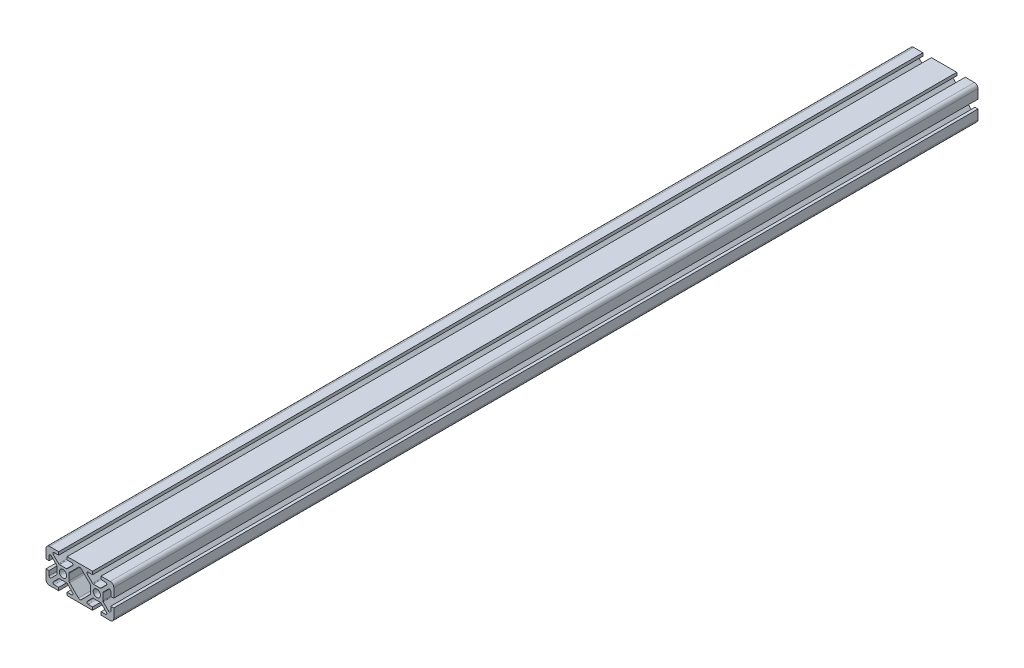
SolidWorks part; units mm, degrees
ref_plane "Front Plane" through (0, 0, 0) normal (0, 0, 1) x (1, 0, 0)
ref_plane "Top Plane" through (0, 0, 0) normal (0, 1, 0) x (1, 0, 0)
ref_plane "Right Plane" through (0, 0, 0) normal (1, 0, 0) x (0, 0, -1)
sketch "Sketch1" plane through (0, 0, 0) normal (0, 0, 1) x (1, 0, 0)
  line L0 (10, 10) -> (10, -10) construction
  line L1 (-20, 0) -> (20, 0) construction
  line L2 (12.5, -10) -> (20, -10)
  line L3 (20, -10) -> (20, -2.5)
  line L4 (12.5, -10) -> (12.5, -8.2134)
  line L5 (12.5, -8.2134) -> (16.95, -8.2134)
  line L6 (16.95, -8.2134) -> (12.3366, -3.6)
  line L7 (10, 0) -> (20, -10) construction
  line L8 (20, -2.5) -> (18.2134, -2.5)
  line L9 (18.2134, -2.5) -> (18.2134, -6.95)
  line L10 (18.2134, -6.95) -> (13.6, -2.3366)
  line L11 (15.9067, -4.6433) -> (14.6433, -5.9067) construction
  line L12 (0, 10) -> (0, -10) construction
  line L13 (0, -10) -> (-20, -10) construction
  line L14 (-10, 10) -> (10, 10) construction
  line L15 (20, 2.5) -> (20, -2.5) construction
  circle A0 centre (10, 0) radius 2.15
  arc A1 (15.5015, -8.2134) -> (15.9257, -7.1891) centre (15.5015, -7.6134) ccw construction
  point P8 (10, -3.6)
  point P16 (15.275, -5.275)
  point P30 (20, 0)
  dimension "Center Hole Diameter" = 4.3
  dimension "D3" = 0.6
  dimension "Rail Width" = 20
  dimension "T-Slot Width" = 5
  dimension "Slot Depth" = 6.4
  dimension "Rail Height" = 40
  dimension "Inner Slot Width" = 13.9
  dimension "Hole Spacing" = 20
sketch "Sketch2" plane through (0, 0, 0) normal (1, 0, 0) x (0, 0, -1)
  line L0 (-1524, -10) -> (1524, -10) construction
  line L1 (-1484, 0) -> (1484, 0) construction
  point P6 (-1484, 0)
  point P8 (1484, 0)
  dimension "Length" = 3048
  dimension "D1" = 40
sketch "Sketch3" plane through (0, 0, 0) normal (0, 0, 1) x (1, 0, 0)
  line L0 (12.5, -10) -> (17.9, -10)
  line L1 (12.5, -10) -> (20, -10) construction
  line L2 (12.5, -10) -> (12.5, -8.2134) construction
  line L3 (12.5, -8.2134) -> (16.95, -8.2134) construction
  line L4 (12.5, -8.2134) -> (12.5, -10)
  line L5 (12.5, -8.2134) -> (16.95, -8.2134)
  line L6 (10, -3.6) -> (12.3366, -3.6)
  line L7 (16.95, -8.2134) -> (12.3366, -3.6) construction
  line L8 (12.3366, -3.6) -> (16.95, -8.2134)
  line L9 (20, -10) -> (20, -2.5) construction
  line L10 (18.2134, -6.95) -> (13.6, -2.3366) construction
  line L11 (18.2134, -2.5) -> (18.2134, -6.95) construction
  line L12 (18.2134, -6.95) -> (18.2134, -2.5)
  line L13 (20, -2.5) -> (18.2134, -2.5) construction
  line L14 (18.2134, -2.5) -> (20, -2.5)
  line L15 (20, -2.5) -> (20, -7.9)
  line L16 (18.2134, -6.95) -> (13.6, -2.3366)
  line L17 (13.6, 0) -> (13.6, -2.3366)
  line L18 (-20, 0) -> (20, 0) construction
  line L19 (10, -3.6) -> (10, -2.15)
  line L20 (10, 10) -> (10, -10) construction
  line L21 (13.6, 0) -> (12.15, 0)
  arc A5 (17.9, -10) -> (20, -7.9) centre (17.9, -7.9) ccw
  circle A10 centre (10, 0) radius 2.15 construction
  arc A11 (10, -2.15) -> (12.15, 0) centre (10, 0) ccw
  dimension "D1" = 2.1
extrude "Boss-Extrude1" add sketch "Sketch3" along normal mid plane 3048
sketch "Sketch4" plane through (0, 0, 0) normal (0, 0, 1) x (1, 0, 0)
  line L0 (10, -3.6) -> (7.6634, -3.6)
  line L4 (7.6634, -3.6) -> (3.05, -8.2134)
  line L5 (3.05, -8.2134) -> (7.5, -8.2134)
  line L6 (7.5, -8.2134) -> (7.5, -10)
  line L18 (7.5, -10) -> (0, -10)
  line L19 (12.5, -10) -> (12.5, -8.2134) construction
  line L20 (12.5, -8.2134) -> (16.95, -8.2134) construction
  line L21 (10, -3.6) -> (12.3366, -3.6) construction
  line L22 (16.95, -8.2134) -> (12.3366, -3.6) construction
  line L23 (0, -8.7366) -> (6.4, -2.3366)
  line L24 (0, 10) -> (0, -10) construction
  line L25 (6.4, -2.3366) -> (6.4, 0)
  line L26 (-20, 0) -> (20, 0) construction
  line L27 (6.4, 0) -> (7.85, 0)
  line L28 (13.6, 0) -> (12.15, 0) construction
  line L29 (0, -8.7366) -> (0, -10)
  line L30 (10, -2.15) -> (10, -3.6)
  circle A4 centre (10, 0) radius 2.15 construction
  arc A5 (7.85, 0) -> (10, -2.15) centre (10, 0) ccw
extrude "Boss-Extrude2" add sketch "Sketch4" along normal mid plane 3048
mirror "Mirror1" about plane through (0, 0, 0) normal (1, 0, 0) of bodies 137 134
mirror "Mirror2" about plane through (0, 0, 0) normal (0, 1, 0) of bodies 135
fillet "Fillet1" radius 0.75 24 edges at (-7.6634, -3.6, 0) (-12.3366, -3.6, 0) (12.3366, -3.6, 0) (7.6634, -3.6, 0) (-3.05, -8.2134, 0) (-18.2134, -6.95, 0) (-16.95, -8.2134, 0) (-13.6, -2.3366, 0) (-18.2134, 6.95, 0) (-16.95, 8.2134, 0) (-12.3366, 3.6, 0) (-7.6634, 3.6, 0) (-13.6, 2.3366, 0) (-3.05, 8.2134, 0) (3.05, 8.2134, 0) (13.6, -2.3366, 0) (13.6, 2.3366, 0) (7.6634, 3.6, 0) (12.3366, 3.6, 0) (18.2134, 6.95, 0) (16.95, 8.2134, 0) (18.2134, -6.95, 0) (16.95, -8.2134, 0) (3.05, -8.2134, 0)
fillet "Fillet2" radius 1.25 6 edges at (0, -8.7366, 0) (-6.4, -2.3366, 0) (0, 8.7366, 0) (-6.4, 2.3366, 0) (6.4, -2.3366, 0) (6.4, 2.3366, 0)
sketch "Sketch5" plane through (-20, 0, 0) normal (-1, 0, 0) x (0, 0, 1)
  line L0 (1524, -10) -> (-1524, -10) construction
  line L1 (1524, 10) -> (-1014, 10)
  line L2 (1524, 10) -> (1524, -10)
  line L3 (1524, -10) -> (-1014, -10)
  line L4 (-1014, 10) -> (-1014, -10)
  line L5 (-1524, 7.9) -> (-1524, 2.5) construction
  dimension "D1" = 510
extrude "Cut-Extrude1" cut sketch "Sketch5" against normal through all
equation "\"D1@Sketch3\" = \"D3@Sketch1\" * 3.5"
equation "\"D1@Boss-Extrude1\" = \"Length@Sketch2\""
equation "\"D1@Boss-Extrude2\" = \"Length@Sketch2\""
equation "\"D1@Sketch2\"=\"Rail Height@Sketch1\""
